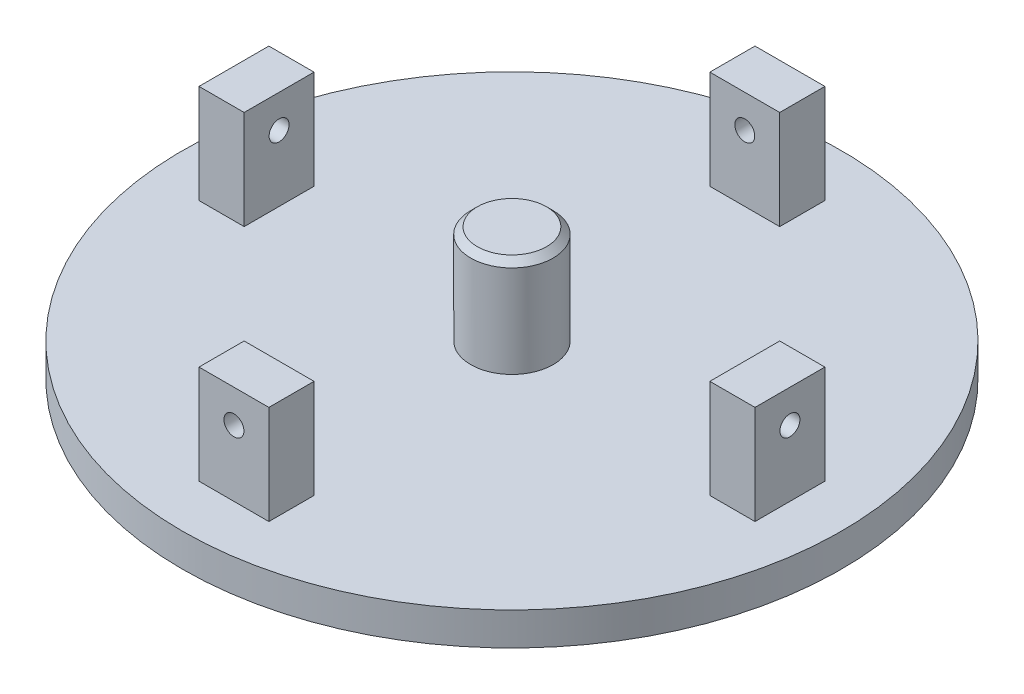
SolidWorks part; units mm, degrees
ref_plane "Front Plane" through (0, 0, 0) normal (0, 0, 1) x (1, 0, 0)
ref_plane "Top Plane" through (0, 0, 0) normal (0, 1, 0) x (1, 0, 0)
ref_plane "Right Plane" through (0, 0, 0) normal (1, 0, 0) x (0, 0, -1)
sketch "Sketch1" plane through (0, 0, 0) normal (0, 1, 0) x (1, 0, 0)
  circle A0 centre (0, 0) radius 100
  dimension "D1" = 200
extrude "Boss-Extrude1" add sketch "Sketch1" along normal blind 10
sketch "Sketch2" plane through (0, 10, 0) normal (0, 1, 0) x (1, 0, 0)
  line L0 (0, 100) -> (0, 0) construction
  line L1 (0, 0) -> (100, 0) construction
  line L2 (10.6, -70.65) -> (10.6, -84.35)
  line L3 (70.65, 10.6) -> (84.35, 10.6)
  line L4 (70.65, 10.6) -> (70.65, -10.6)
  line L5 (70.65, -10.6) -> (84.35, -10.6)
  line L6 (84.35, 10.6) -> (84.35, -10.6)
  line L7 (70.65, 10.6) -> (84.35, -10.6) construction
  line L8 (70.65, -10.6) -> (84.35, 10.6) construction
  line L9 (10.6, -84.35) -> (-10.6, -84.35)
  line L10 (-10.6, -70.65) -> (-10.6, -84.35)
  line L11 (10.6, -70.65) -> (-10.6, -70.65)
  line L12 (-70.65, -10.6) -> (-84.35, -10.6)
  line L13 (-84.35, -10.6) -> (-84.35, 10.6)
  line L14 (-70.65, 10.6) -> (-84.35, 10.6)
  line L15 (-70.65, -10.6) -> (-70.65, 10.6)
  line L16 (-10.6, 70.65) -> (-10.6, 84.35)
  line L17 (-10.6, 84.35) -> (10.6, 84.35)
  line L18 (10.6, 70.65) -> (10.6, 84.35)
  line L19 (-10.6, 70.65) -> (10.6, 70.65)
  circle A0 centre (0, 0) radius 100 construction
  point P7 (77.5, 0)
  dimension "D1" = 13.7
  dimension "D2" = 21.2
  dimension "D3" = 77.5
  dimension "D4" = 4
extrude "Boss-Extrude2" add sketch "Sketch2" along normal blind 30
sketch "Sketch3" plane through (-84.35, 0, 0) normal (-1, 0, 0) x (0, 0, 1)
  line L0 (-10.6, 10) -> (10.6, 10) construction
  circle A0 centre (0, 30) radius 3.025
  dimension "D2" = 6.05
  dimension "D1" = 20
extrude "Cut-Extrude1" cut sketch "Sketch3" against normal blind 190
sketch "Sketch4" plane through (0, 0, 84.35) normal (0, 0, 1) x (1, 0, 0)
  line L0 (-10.6, 10) -> (10.6, 10) construction
  circle A0 centre (0, 30) radius 3.025
  dimension "D2" = 6.05
  dimension "D1" = 20
extrude "Cut-Extrude2" cut sketch "Sketch4" against normal blind 190
sketch "Sketch5" plane through (0, 10, 0) normal (0, 1, 0) x (1, 0, 0)
  circle A0 centre (0, 0) radius 12.5
  dimension "D1" = 25
extrude "Boss-Extrude3" add sketch "Sketch5" along normal up to surface (30 mm away) up to face at (-77.5, 40, 0)
chamfer "Chamfer1" distance 2 angle 45 1 edges at (0, 40, -12.5)
